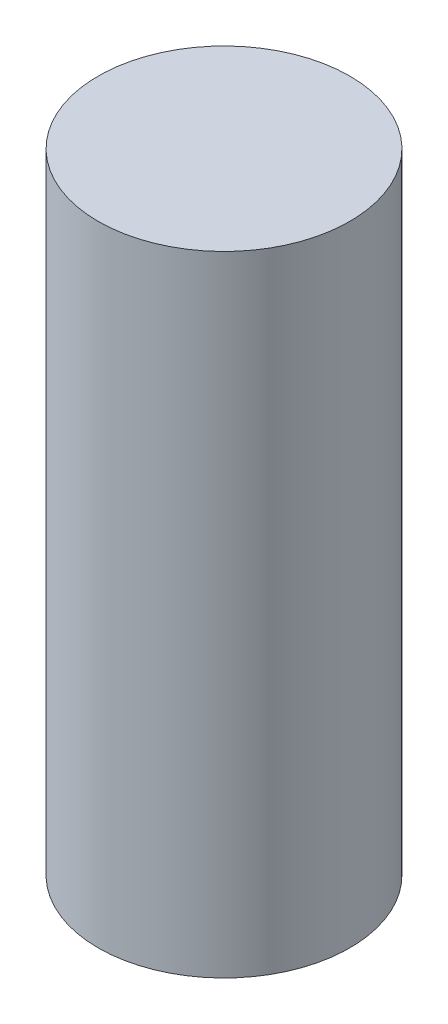
SolidWorks part; units mm, degrees
ref_plane "Front Plane" through (0, 0, 0) normal (0, 0, 1) x (1, 0, 0)
ref_plane "Top Plane" through (0, 0, 0) normal (0, 1, 0) x (1, 0, 0)
ref_plane "Right Plane" through (0, 0, 0) normal (1, 0, 0) x (0, 0, -1)
sketch "Sketch1" plane through (0, 0, 0) normal (0, 1, 0) x (1, 0, 0)
  circle A0 centre (0, 0) radius 30
  dimension "D1" = 60
extrude "Boss-Extrude1" add sketch "Sketch1" along normal blind 150
